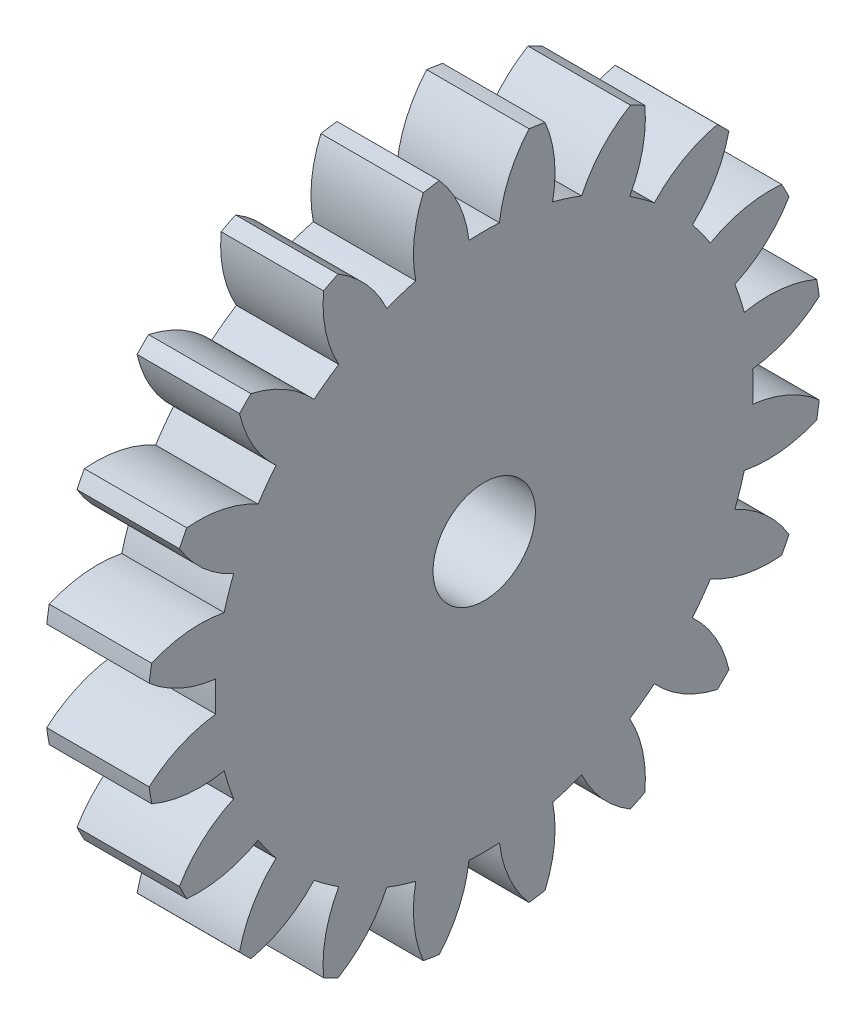
SolidWorks part; units mm, degrees
ref_plane "Plane1" through (0, 0, 0) normal (0, 0, 1) x (1, 0, 0)
ref_plane "Plane2" through (0, 0, 0) normal (0, 1, 0) x (1, 0, 0)
ref_plane "Plane3" through (0, 0, 0) normal (1, 0, 0) x (0, 0, -1)
other "Configuration Table"
sketch "HoldingSke" plane through (0, 0, 0) normal (0, 1, 0) x (1, 0, 0)
  line L0 (0, 0) -> (0.6265, -0.228)
  line L1 (-15, 0) -> (100, 0) construction
  line L2 (0, 0) -> (-2.1039, 2.3779)
  line L3 (0, 0) -> (-11.863, 4.5341)
  line L4 (0, 0) -> (8.1152, 2.9537)
  line L5 (0, 0) -> (-46.8476, -17.4728)
  line L6 (0, 0) -> (-4.1448, -2.7965)
  line L7 (-2.1039, 2.3779) -> (8.6586, 51.2059)
  line L8 (-76.2, 54.61) -> (-75.3, 54.61)
  line L9 (-71.009, 38.7566) -> (-53.1078, 45.2721)
  line L10 (-76.2, 71.12) -> (104.1128, 71.12)
  line L11 (0, 0) -> (-5, 0)
  line L12 (-76.2, 101.6) -> (-76.147, 101.6)
  line L13 (24.9733, 27.94) -> (52.9518, 28.4284)
  line L14 (24.9733, 27.94) -> (24.9743, 27.94)
  line L15 (24.9733, 27.94) -> (100.4006, 29.5858)
  line L16 (-63.627, -1.5) -> (-12.827, -1.5)
  circle A0 centre (0, 0) radius 2.5
  circle A1 centre (0, 0) radius 13.124
  circle A2 centre (0, 0) radius 37.5
  circle A3 centre (0, 0) radius 2.5
  dimension "Hub_dia" = 75
  dimension "Bore" = 5
  dimension "MBD" = 5
  dimension "Pitch" = 0.6667
  dimension "Overall_len" = 50
  dimension "Thickness" = 5
  dimension "OAL" = 50.0001
  dimension "T_dim" = 0.9
  dimension "Ap" = 20
  dimension "H" = 19.05
  dimension "Pitch_radius" = 180.3128
  dimension "Width" = 5
  dimension "Backlash" = 0.053
  dimension "Addendum_fac" = 1
  dimension "Dedendum_fac" = 1.25
  dimension "Clearance_fac" = 0.25
  dimension "Dedendum_add" = 0.001
  dimension "Module" = 1.5
sketch "BasProSke" plane through (0, 0, 0) normal (0, 1, 0) x (1, 0, 0)
  line L0 (-10, 0) -> (60, 0) construction
  line L1 (0, 0) -> (0, 16.5)
  line L2 (0, 0) -> (5, 0)
  line L3 (5, 0) -> (5, 16.5)
  line L4 (5, 16.5) -> (0, 16.5)
  dimension "Thickness" = 5
revolve "Base-Revolve" add sketch "BasProSke" angle 360 about L0
sketch "TooCutSke" plane through (0, 0, 0) normal (1, 0, 0) x (0, 0, -1)
  line L1 (0, 0) -> (0, 107) construction
  line L2 (0, 0) -> (-1.2696, 14.9462) construction
  line L3 (0, 0) -> (-4.6808, 29.5532) construction
  line L4 (-1.2696, 14.9462) -> (-2.3404, 14.7766) construction
  arc A0 (0.7438, 13.1029) -> (-0.7438, 13.1029) centre (0, 0) ccw
  arc A1 (2.21, 16.377) -> (-2.21, 16.377) centre (0, 0) ccw
  circle A2 centre (0, 0) radius 15 construction
  circle A3 centre (0, 0) radius 14.0954 construction
  arc A4 (-0.7438, 13.1029) -> (-2.21, 16.377) centre (-6.7025, 12.3999) ccw
  arc A5 (2.21, 16.377) -> (0.7438, 13.1029) centre (6.7025, 12.3999) ccw
extrude "ToothCut" cut sketch "TooCutSke" along normal through all
fillet "Breaks" [suppressed] radius 0.03
fillet "RootFillets" [suppressed] radius 0.376
pattern_circular "TeethCuts" count 20 every 18 about axis through (-10, 0, 0) along (1, 0, 0) of "ToothCut", "RootFillets", "Breaks"
sketch "HubNeaOneSke" plane through (0, 0, 0) normal (-1, 0, 0) x (0, 0, 1)
  circle A0 centre (0, 0) radius 13.124
extrude "HubNearOne" [suppressed] add sketch "HubNeaOneSke" along normal blind 45.0001
sketch "HubNeaBotSke" plane through (0, 0, 0) normal (-1, 0, 0) x (0, 0, 1)
  circle A0 centre (0, 0) radius 13.124
extrude "HubNearBoth" [suppressed] add sketch "HubNeaBotSke" along normal blind 22.5
ref_plane "FarPln" through (5, 0, 0) normal (1, 0, 0) x (0, 0, -1)
sketch "HubFarSke" plane through (5, 0, 0) normal (1, 0, 0) x (0, 0, -1)
  circle A0 centre (0, 0) radius 13.124
extrude "HubFar" [suppressed] add sketch "HubFarSke" along normal blind 22.5
sketch "BorSke" plane through (0, 0, 0) normal (1, 0, 0) x (0, 0, -1)
  circle A0 centre (0, 0) radius 2.5
  dimension "Diameter" = 5
extrude "Bore" cut sketch "BorSke" along normal mid plane 100.0001
sketch "KeySke" plane through (0, 0, 0) normal (1, 0, 0) x (0, 0, -1)
  line L0 (-1, 0) -> (-1, 3.4)
  line L1 (-1, 3.4) -> (1, 3.4)
  line L2 (1, 3.4) -> (1, 0)
  line L3 (0, 0) -> (0, 34) construction
  line L4 (-1, 0) -> (1, 0)
  dimension "Offset" = 3.4
  dimension "Width" = 2
extrude "Keyway" [suppressed] cut sketch "KeySke" along normal mid plane 100.0001
pattern_circular "Keyway2" [suppressed] count 2 every 90 about axis through (-10, 0, 0) along (1, 0, 0)
equation "' \"Module@HoldingSke\" = 6.35"
equation "' \"Num_teeth@HoldingSke\" = 12"
equation "' \"Ap@HoldingSke\" =  20"
equation "' \"Ap@HoldingSke\" = 20"
equation "' \"Width@HoldingSke\" = 0.5 * 25.4"
equation "' \"Hub_dia@HoldingSke\"= 1 * 25.4"
equation "' \"Hub_dia@HoldingSke\" = 1 * 25.4"
equation "' \"Overall_len@HoldingSke\" = 1.0 * 25.4"
equation "' \"Bore@HoldingSke\" = 0.75 * 25.4"
equation "' \"T_dim@HoldingSke\" = 0.1 * 25.4"
equation "' \"Width@KeySke\" = 0.25 * 25.4"
equation "' \"Show_teeth@HoldingSke\" = 13"
equation "' \"Backlash@HoldingSke\" = 0.009 * 25.4"
equation "' \"Addendum_fac@HoldingSke\" = 1.0"
equation "' \"Dedendum_fac@HoldingSke\" = 1.25"
equation "' \"Dedendum_add@HoldingSke\" = 0.00005 * 25.4"
equation "' \"Clearance_fac@HoldingSke\" = 0.25"
equation "\"Pitch@HoldingSke\" = 1 / \"Module@HoldingSke\""
equation "\"Overcut_dia@TooCutSke\" = (\"Num_teeth@HoldingSke\" + 2 * \"Addendum_fac@HoldingSke\") / \"Pitch@HoldingSke\" + 0.002 * 25.4"
equation "\"Pitch_dia@TooCutSke\" = \"Num_teeth@HoldingSke\" / \"Pitch@HoldingSke\""
equation "\"Base_dia@TooCutSke\" = \"Num_teeth@HoldingSke\" / \"Pitch@HoldingSke\" * cos((\"Ap@HoldingSke\"  * 3.14159265 / 180))"
equation "\"Root_dia@TooCutSke\" = (\"Num_teeth@HoldingSke\" + 2) / \"Pitch@HoldingSke\" - 2 * (\"Addendum_fac@HoldingSke\" + \"Dedendum_fac@HoldingSke\") / \"Pitch@HoldingSke\" - \"Dedendum_add@HoldingSke\" * 2"
equation "\"Half_ang@TooCutSke\" = 180 / \"Num_teeth@HoldingSke\""
equation "\"Half_CT@TooCutSke\" = \"Num_teeth@HoldingSke\" / \"Pitch@HoldingSke\" * sin((3.14159265 / 2 / \"Num_teeth@HoldingSke\")) / 2 - 7 * \"Backlash@HoldingSke\" / 4"
equation "\"Flank_rad@TooCutSke\" = \"Num_teeth@HoldingSke\" / \"Pitch@HoldingSke\" / 5"
equation "\"Radius@RootFillets\" = \"Clearance_fac@HoldingSke\" / \"Pitch@HoldingSke\" + \"Dedendum_add@HoldingSke\""
equation "\"Break_rad@Breaks\" = 0.02 / \"Pitch@HoldingSke\""
equation "\"Thickness@HoldingSke\" = \"Width@HoldingSke\""
equation "\"OAL@HoldingSke\" = \"Thickness@HoldingSke\""
equation "\"MHD@HoldingSke\" = (\"Num_teeth@HoldingSke\" + 2) / \"Pitch@HoldingSke\" - 2 * (\"Addendum_fac@HoldingSke\" + \"Dedendum_fac@HoldingSke\")  / \"Pitch@HoldingSke\" - \"Dedendum_add@HoldingSke\" * 2"
equation "\"MBD@HoldingSke\" = (\"Num_teeth@HoldingSke\" + 2) / \"Pitch@HoldingSke\" - 2 * (\"Addendum_fac@HoldingSke\" + \"Dedendum_fac@HoldingSke\")  / \"Pitch@HoldingSke\" - \"Dedendum_add@HoldingSke\" * 2 - 0.002 * 25.4"
equation "\"MHD@HoldingSke\" = ((sgn( \"MHD@HoldingSke\" - \"Hub_dia@HoldingSke\" )-1)*( \"MHD@HoldingSke\" - \"Hub_dia@HoldingSke\" ))/-2+ \"Hub_dia@HoldingSke\""
equation "\"MBD@HoldingSke\" = ((sgn( \"MBD@HoldingSke\" - \"Bore@HoldingSke\" )-1)*( \"MBD@HoldingSke\" - \"Bore@HoldingSke\" ))/-2+ \"Bore@HoldingSke\""
equation "\"OAL@HoldingSke\" = ((sgn( \"OAL@HoldingSke\" - \"Overall_len@HoldingSke\" )+1)*( \"OAL@HoldingSke\" - \"Overall_len@HoldingSke\" ))/2 + \"Overall_len@HoldingSke\" + 0.000002 * 25.4"
equation "\"Num_teeth@TeethCuts\" = int( \"Show_teeth@HoldingSke\" ) + 1"
equation "\"Num_teeth@TeethCuts\" = ((sgn( \"Num_teeth@TeethCuts\" - \"Num_teeth@HoldingSke\" )-1)*( \"Num_teeth@TeethCuts\" - \"Num_teeth@HoldingSke\" ))/-2+ \"Num_teeth@HoldingSke\""
equation "\"Num_teeth@TeethCuts\" = ((sgn( \"Num_teeth@TeethCuts\" - 2.0)+1)*( \"Num_teeth@TeethCuts\" - 2.0))/2 +2.0"
equation "\"Angle@TeethCuts\" = 360.0 / \"Num_teeth@HoldingSke\""
equation "\"Diameter@BasProSke\" = (\"Num_teeth@HoldingSke\" + 2 * \"Addendum_fac@HoldingSke\") / \"Pitch@HoldingSke\""
equation "\"Thickness@BasProSke\"  = \"Thickness@HoldingSke\""
equation "' \"Fillet_rad@BasProSke\" =  \"Thickness@HoldingSke\" * 0.05"
equation "' \"Fillet_rad@BasProSke\" = \"Thickness@HoldingSke\" * 0.05"
equation "\"MHD@HoldingSke\" = ((sgn( \"MHD@HoldingSke\" - \"Root_dia@TooCutSke\" )-1)*( \"MHD@HoldingSke\" - \"Root_dia@TooCutSke\" ))/-2+ \"Root_dia@TooCutSke\""
equation "\"Diameter@HubNeaOneSke\" = \"MHD@HoldingSke\""
equation "\"Length@HubNearOne\" = \"OAL@HoldingSke\" - \"Thickness@BasProSke\""
equation "\"Diameter@HubNeaBotSke\" = \"MHD@HoldingSke\""
equation "\"Length@HubNearBoth\" = ( \"OAL@HoldingSke\" - \"Thickness@BasProSke\" ) / 2.0"
equation "\"Thickness@FarPln\" = \"Thickness@BasProSke\""
equation "\"Diameter@HubFarSke\" = \"MHD@HoldingSke\""
equation "\"Length@HubFar\" = ( \"OAL@HoldingSke\" - \"Thickness@BasProSke\" ) / 2.0"
equation "\"Diameter@BorSke\" = \"MBD@HoldingSke\""
equation "\"D1@Bore\" = \"OAL@HoldingSke\" * 2.0"
equation "\"D1@Keyway\" = \"OAL@HoldingSke\" * 2.0"
equation "\"Offset@KeySke\" = \"T_dim@HoldingSke\" + \"MBD@HoldingSke\" / 2.0"
